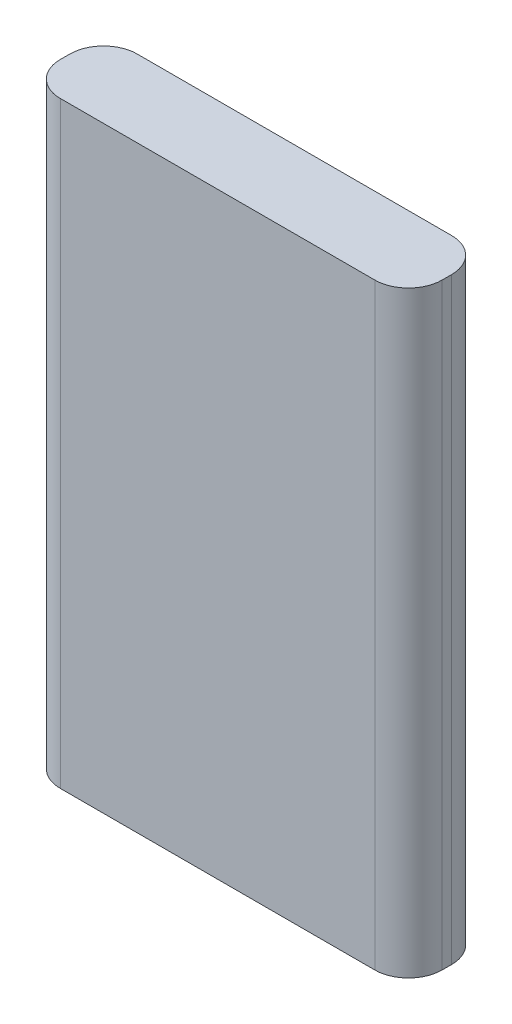
SolidWorks part; units mm, degrees
ref_plane "Спереди" through (0, 0, 0) normal (0, 0, 1) x (1, 0, 0)
ref_plane "Сверху" through (0, 0, 0) normal (0, 1, 0) x (1, 0, 0)
ref_plane "Справа" through (0, 0, 0) normal (1, 0, 0) x (0, 0, -1)
sketch "Эскиз1" plane through (0, 0, 0) normal (0, 1, 0) x (1, 0, 0)
  line L1 (-14, 3.425) -> (14, 3.425)
  line L2 (-17, 0.425) -> (-17, -0.425)
  line L3 (-14, -3.425) -> (14, -3.425)
  line L4 (17, 0.425) -> (17, -0.425)
  line L5 (-17, 3.425) -> (17, -3.425) construction
  line L6 (-17, -3.425) -> (17, 3.425) construction
  arc A0 (14, 3.425) -> (17, 0.425) centre (14, 0.425) cw
  arc A1 (14, -3.425) -> (17, -0.425) centre (14, -0.425) ccw
  arc A2 (-17, -0.425) -> (-14, -3.425) centre (-14, -0.425) ccw
  arc A3 (-17, 0.425) -> (-14, 3.425) centre (-14, 0.425) cw
  point P0 (0, 0)
  dimension "D3" = 3
  dimension "D1" = 34
  dimension "D2" = 6.85
extrude "Бобышка-Вытянуть1" add sketch "Эскиз1" along normal blind 53.2
